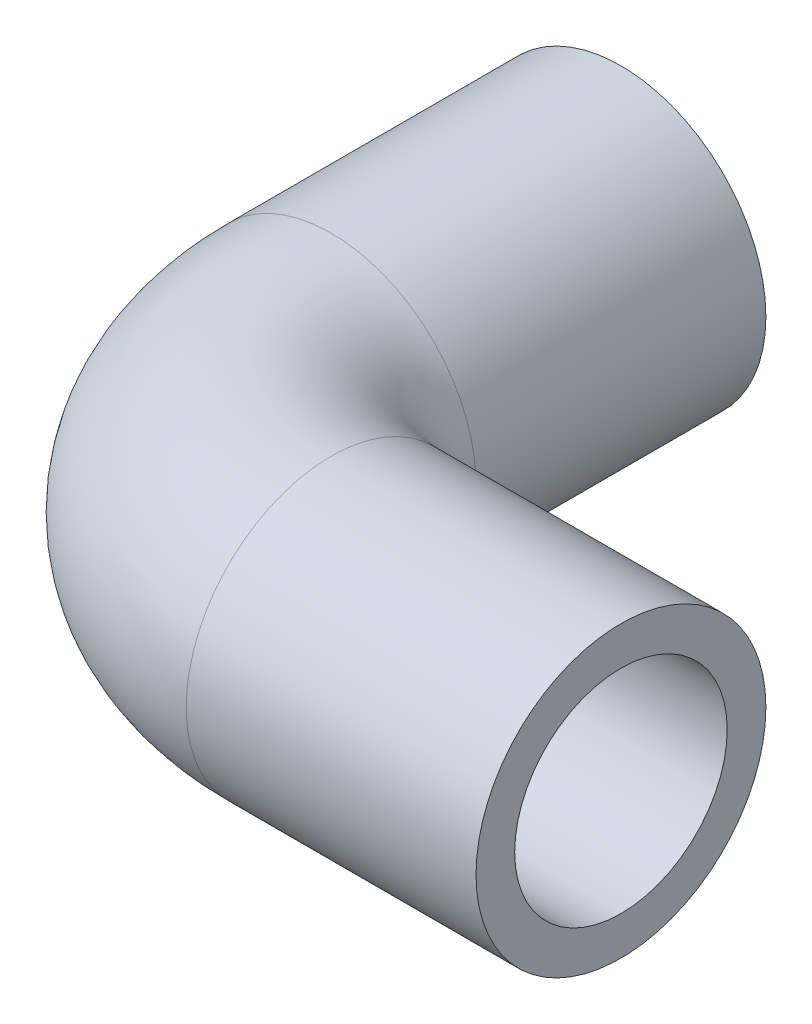
SolidWorks part; units mm, degrees
material "Plain Carbon Steel"
ref_plane "Front Plane" through (0, 0, 0) normal (0, 0, 1) x (1, 0, 0)
ref_plane "Top Plane" through (0, 0, 0) normal (0, 1, 0) x (1, 0, 0)
ref_plane "Right Plane" through (0, 0, 0) normal (1, 0, 0) x (0, 0, -1)
sketch "Sketch1" plane through (0, 0, 0) normal (0, 1, 0) x (1, 0, 0)
  line L0 (0, 0) -> (-75, 0)
  line L1 (-125, 50) -> (-125, 125)
  arc A0 (-75, 0) -> (-125, 50) centre (-75, 50) cw
  dimension "D1" = 75
  dimension "D2" = 75
  dimension "D3" = 50
  dimension "D4" = 50
sweep "Sweep1" add path "Sketch1" circular profile diameter 75 parameters "D3"=75
shell "Shell1" thickness 10
sketch "Sketch2" plane through (0, 0, -125) normal (0, 0, -1) x (-1, 0, 0)
  line L0 (125, 27.5) -> (125, 37.5)
  circle A0 centre (125, 0) radius 27.5
  circle A1 centre (125, 0) radius 37.5 construction
  dimension "D1" = 10
extrude "Cut-Extrude1" cut sketch "Sketch2" against normal up to next contours A0
